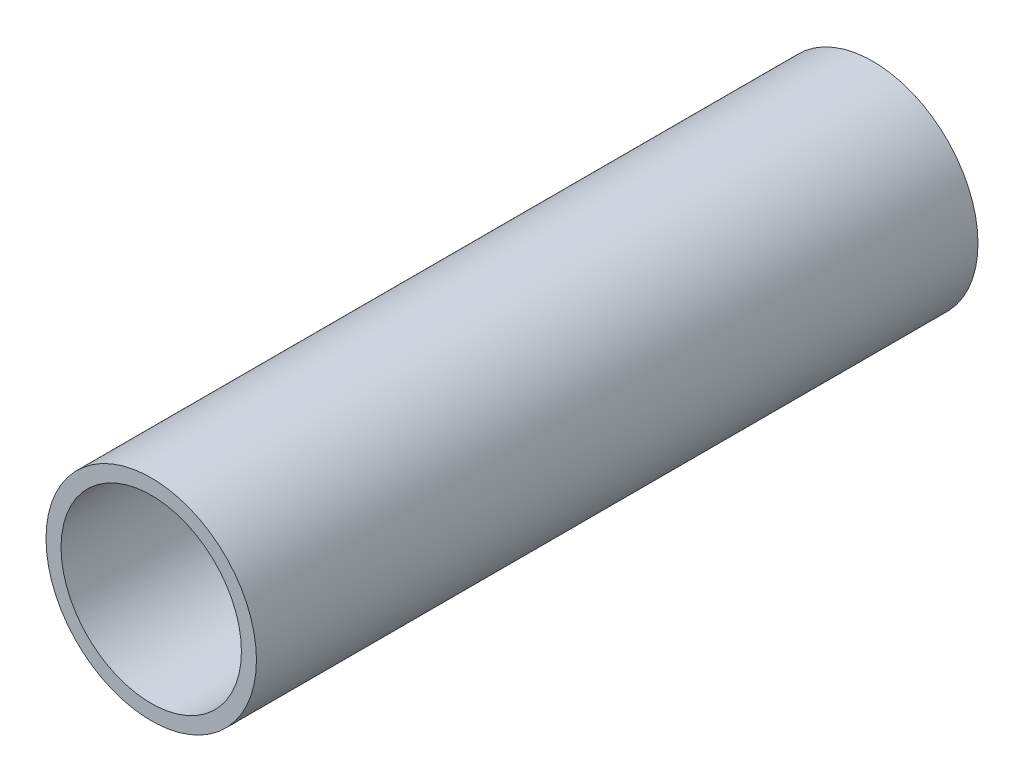
SolidWorks part; units mm, degrees
ref_plane "Front Plane" through (0, 0, 0) normal (0, 0, 1) x (1, 0, 0)
ref_plane "Top Plane" through (0, 0, 0) normal (0, 1, 0) x (1, 0, 0)
ref_plane "Right Plane" through (0, 0, 0) normal (1, 0, 0) x (0, 0, -1)
sketch "Sketch1" plane through (0, 0, 0) normal (0, 0, 1) x (1, 0, 0)
  circle A0 centre (0, 0) radius 22.225
  dimension "D1" = 44.45
extrude "Boss-Extrude1" add sketch "Sketch1" along normal blind 152.4
sketch "Sketch2" plane through (0, 0, 152.4) normal (0, 0, 1) x (1, 0, 0)
  circle A0 centre (0, 0) radius 19.05
  dimension "D1" = 38.1
extrude "Cut-Extrude1" cut sketch "Sketch2" against normal through all
